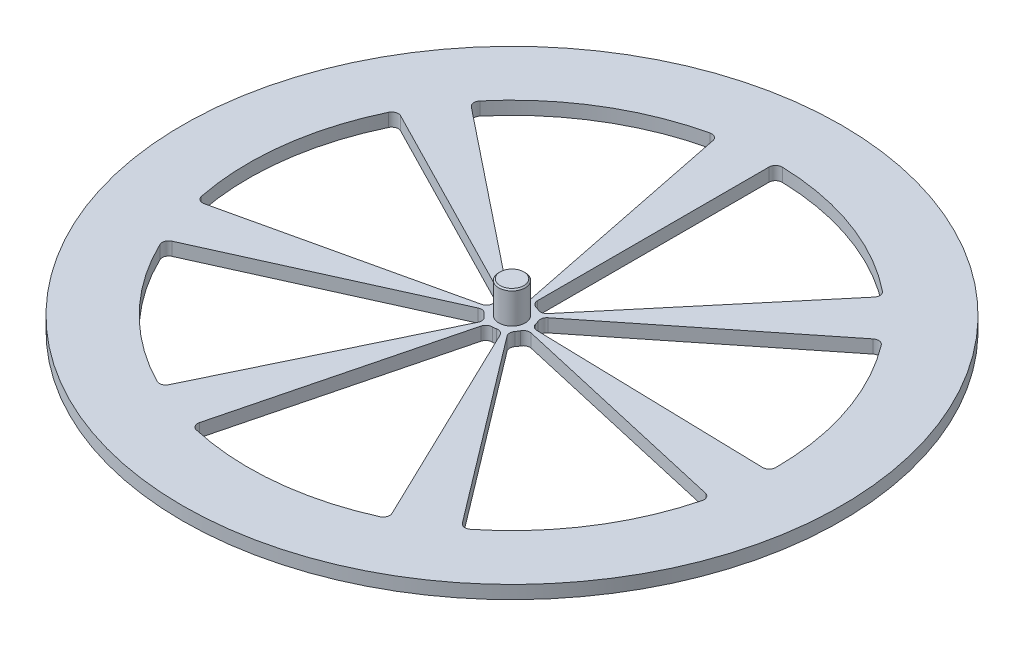
SolidWorks part; units mm, degrees
ref_plane "Front Plane" through (0, 0, 0) normal (0, 0, 1) x (1, 0, 0)
ref_plane "Top Plane" through (0, 0, 0) normal (0, 1, 0) x (1, 0, 0)
ref_plane "Right Plane" through (0, 0, 0) normal (1, 0, 0) x (0, 0, -1)
sketch "Sketch1" plane through (0, 0, 0) normal (0, 1, 0) x (1, 0, 0)
  circle A0 centre (0, 0) radius 250
  dimension "D1" = 500
extrude "Boss-Extrude1" add sketch "Sketch1" along normal blind 10
sketch "Sketch2" plane through (0, 10, 0) normal (0, 1, 0) x (1, 0, 0)
  line L0 (0, 15) -> (0, 200)
  line L1 (9.6418, 11.4907) -> (128.5575, 153.2089)
  arc A0 (9.6418, 11.4907) -> (0, 15) centre (0, 0) ccw
  arc A1 (128.5575, 153.2089) -> (0, 200) centre (0, 0) ccw
  circle A2 centre (0, 0) radius 250 construction
  dimension "D1" = 15
  dimension "D2" = 50
  dimension "D3" = 40
extrude "Cut-Extrude1" cut sketch "Sketch2" against normal through all
fillet "Fillet1" radius 5 4 edges at (128.5575, 5, -153.2089) (0, 5, -200) (9.6418, 5, -11.4907) (0, 5, -15)
pattern_circular "CirPattern1" count 7 over 360 about axis through (0, 0, 0) along (0, 1, 0) of "Cut-Extrude1", "Fillet1"
sketch "Sketch3" plane through (0, 10, 0) normal (0, 1, 0) x (1, 0, 0)
  circle A0 centre (0, 0) radius 10
  dimension "D1" = 20
extrude "Boss-Extrude2" add sketch "Sketch3" along normal blind 24.1
chamfer "Chamfer1" distance 1 angle 45 1 edges at (0, 34.1, 10)
